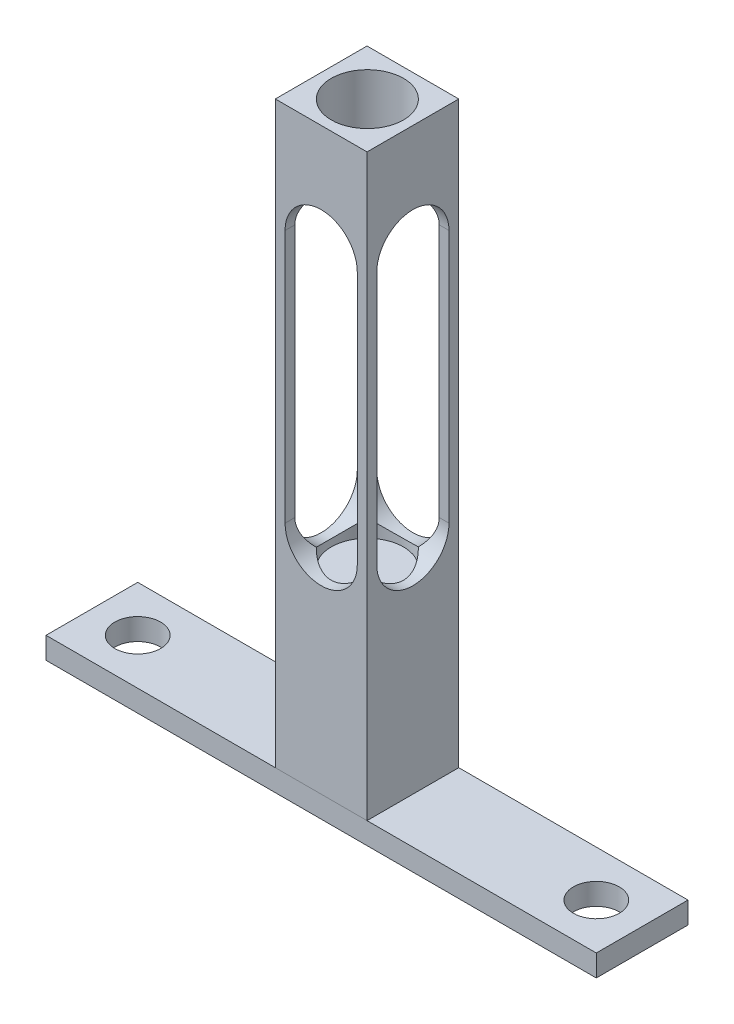
SolidWorks part; units mm, degrees
ref_plane "Front" through (0, 0, 0) normal (0, 0, 1) x (1, 0, 0)
ref_plane "Top" through (0, 0, 0) normal (0, 1, 0) x (1, 0, 0)
ref_plane "Right" through (0, 0, 0) normal (1, 0, 0) x (0, 0, -1)
other "Center of Mass"
sketch "Sketch1" plane through (0, 0, 0) normal (0, 0, 1) x (1, 0, 0)
  line L1 (0, 0) -> (12.7, 0)
  line L2 (0, 0) -> (0, 80.2)
  line L3 (0, 80.2) -> (12.7, 80.2)
  line L4 (12.7, 0) -> (12.7, 80.2)
  dimension "D1" = 80.2
  dimension "D2" = 12.7
extrude "Boss-Extrude1" add sketch "Sketch1" along normal blind 12.7
ref_point "Point1"
sketch "Sketch4" plane through (0, 0, 0) normal (0, -1, 0) x (-1, 0, 0)
  line L1 (31.7558, 0.0009) -> (-44.4442, 0.0009)
  line L2 (31.7558, 0.0009) -> (31.7558, -12.6991)
  line L3 (31.7558, -12.6991) -> (-44.4442, -12.6991)
  line L4 (-44.4442, 0.0009) -> (-44.4442, -12.6991)
  line L5 (31.7558, 0.0009) -> (-44.4442, -12.6991) construction
  line L6 (31.7558, -12.6991) -> (-44.4442, 0.0009) construction
  point P0 (-6.3442, -6.3491)
  dimension "D1" = 12.7
  dimension "D2" = 76.2
extrude "Boss-Extrude3" add sketch "Sketch4" along normal blind 3
sketch "Sketch12" plane through (0, 0, 12.7) normal (0, 0, 1) x (1, 0, 0)
  line L0 (6.35, 30) -> (6.35, 65.1) construction
  line L1 (1.35, 30) -> (1.35, 65.1)
  line L2 (11.35, 30) -> (11.35, 65.1)
  line L3 (44.4442, -3) -> (-31.7558, -3) construction
  line L4 (12.7, 0) -> (12.7, 80.2) construction
  arc A0 (1.35, 30) -> (11.35, 30) centre (6.35, 30) ccw
  arc A1 (11.35, 65.1) -> (1.35, 65.1) centre (6.35, 65.1) ccw
  point P2 (6.35, 47.55)
  dimension "D1" = 33
  dimension "D2" = 6.35
extrude "Cut-Extrude5" cut sketch "Sketch12" against normal blind 23
sketch "Sketch13" plane through (12.7, 0, 0) normal (1, 0, 0) x (0, 0, -1)
  line L0 (-6.35, 30) -> (-6.35, 65.1) construction
  line L1 (-11.35, 30) -> (-11.35, 65.1)
  line L2 (-1.35, 30) -> (-1.35, 65.1)
  line L3 (0.0009, -3) -> (-12.6991, -3) construction
  line L4 (0, 0) -> (0, 80.2) construction
  arc A0 (-11.35, 30) -> (-1.35, 30) centre (-6.35, 30) ccw
  arc A1 (-1.35, 65.1) -> (-11.35, 65.1) centre (-6.35, 65.1) ccw
  point P2 (-6.35, 47.55)
  point P7 (-6.3491, -3)
  dimension "D1" = 33
  dimension "D2" = 6.35
extrude "Cut-Extrude6" cut sketch "Sketch13" against normal blind 23
sketch "Sketch16" plane through (0, 80.2, 0) normal (0, 1, 0) x (1, 0, 0)
  circle A0 centre (6.3943, -6.3483) radius 5
extrude "Cut-Extrude8" cut sketch "Sketch16" against normal blind 56.2
sketch "Sketch17" plane through (0, 0, 0) normal (0, 1, 0) x (1, 0, 0)
  line L0 (-31.7558, 0.0009) -> (44.4442, 0.0009) construction
  line L1 (0, -12.6991) -> (-31.7558, -12.6991) construction
  circle A0 centre (-25.4058, -6.3491) radius 3.175
  point P2 (6.3442, 0.0009)
  dimension "D2" = 31.75
  dimension "D1" = 6.35
extrude "Cut-Extrude9" cut sketch "Sketch17" against normal blind 3
sketch "Sketch18" plane through (0, 0, 0) normal (0, 1, 0) x (1, 0, 0)
  line L0 (-31.7558, 0.0009) -> (44.4442, 0.0009) construction
  line L6 (12.7, -12.7) -> (0, -12.7) construction
  circle A0 centre (38.1, -6.3491) radius 3.175
  point P4 (6.35, -12.7)
  dimension "D1" = 6.35
  dimension "D2" = 31.75
extrude "Cut-Extrude10" cut sketch "Sketch18" against normal blind 3
